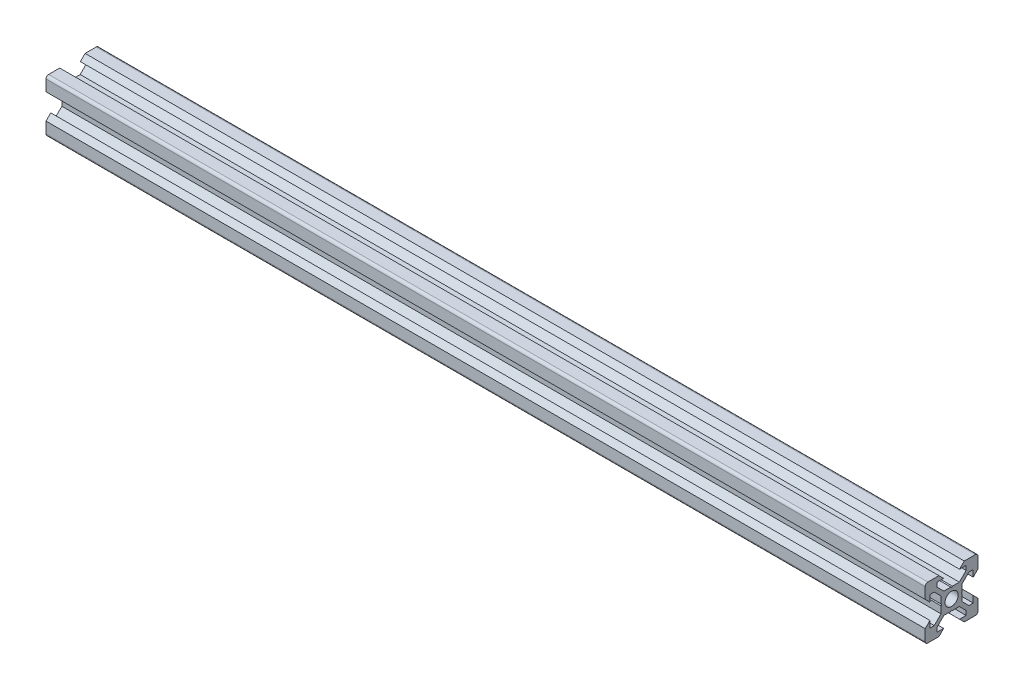
SolidWorks part; units mm, degrees
material "6063-T5"
material "6063-T5"
ref_plane "Plano frontal" through (0, 0, 0) normal (0, 0, 1) x (1, 0, 0)
ref_plane "Plano superior" through (0, 0, 0) normal (0, 1, 0) x (1, 0, 0)
ref_plane "Plano direito" through (0, 0, 0) normal (1, 0, 0) x (0, 0, -1)
sketch "Esboço1" plane through (0, 0, 0) normal (0, 0, 1) x (1, 0, 0)
  line L0 (0, 0) -> (333, 0)
  dimension "D1" = 333
other " C:\\USERS\\USER\\GOOGLE DRIVE\\13. INFORMAÇÕES TÉCNICAS\\BIBLIOTECA SERVIDOR\\PERFIS DE SOLDAGEM\\PERFIL ALUMÍNIO\\QUADRADO\\PF20-11 - PERFIL 2020 V-SLOT - IS MISSING(1)"
ref_plane "Plano1" through (0, 0, 0) normal (1, 0, 0) x (0, 1, 0)
sketch "Sketch11" plane through (0, 0, 0) normal (1, 0, 0) x (0, 1, 0)
  line L0 (-4.8, 10) -> (-3, 8.2)
  line L1 (-3, 8.2) -> (-5.5, 8.2)
  line L2 (-5.5, 8.2) -> (-5.5, 6.5607)
  line L3 (-5.5, 6.5607) -> (-2.9393, 4)
  line L4 (-2.9393, 4) -> (-0.3, 4)
  line L5 (5.5, 6.5607) -> (2.9393, 4)
  line L6 (5.5, 8.2) -> (5.5, 6.5607)
  line L7 (3, 8.2) -> (5.5, 8.2)
  line L8 (4.8, 10) -> (3, 8.2)
  line L9 (-0.3, 4) -> (0, 3.7)
  line L10 (0.3, 4) -> (0, 3.7)
  line L11 (0.3, 4) -> (2.9393, 4)
  line L12 (9, 10) -> (4.8, 10)
  line L13 (10, 4.8) -> (8.2, 3)
  line L14 (10, 4.8) -> (10, 9)
  line L15 (8.2, 3) -> (8.2, 5.5)
  line L16 (8.2, 5.5) -> (6.5607, 5.5)
  line L17 (6.5607, 5.5) -> (4, 2.9393)
  line L18 (4.8, -10) -> (3, -8.2)
  line L19 (3, -8.2) -> (5.5, -8.2)
  line L20 (5.5, -8.2) -> (5.5, -6.5607)
  line L21 (5.5, -6.5607) -> (2.9393, -4)
  line L22 (2.9393, -4) -> (0.3, -4)
  line L23 (0.3, -4) -> (0, -3.7)
  line L24 (-0.3, -4) -> (0, -3.7)
  line L25 (-0.3, -4) -> (-2.9393, -4)
  line L26 (-5.5, -6.5607) -> (-2.9393, -4)
  line L27 (-5.5, -8.2) -> (-5.5, -6.5607)
  line L28 (-3, -8.2) -> (-5.5, -8.2)
  line L29 (-4.8, -10) -> (-3, -8.2)
  line L30 (-10, -4.8) -> (-10, -9)
  line L31 (-10, -4.8) -> (-8.2, -3)
  line L32 (-8.2, -3) -> (-8.2, -5.5)
  line L33 (-8.2, -5.5) -> (-6.5607, -5.5)
  line L34 (-6.5607, -5.5) -> (-4, -2.9393)
  line L35 (-4, -2.9393) -> (-4, -0.3)
  line L36 (-4, -0.3) -> (-3.7, 0)
  line L37 (-4, 0.3) -> (-3.7, 0)
  line L38 (-4, 0.3) -> (-4, 2.9393)
  line L39 (-6.5607, 5.5) -> (-4, 2.9393)
  line L40 (-8.2, 5.5) -> (-6.5607, 5.5)
  line L41 (-8.2, 3) -> (-8.2, 5.5)
  line L42 (-10, 4.8) -> (-8.2, 3)
  line L43 (-4.8, 10) -> (-9, 10)
  line L44 (4, 2.9393) -> (4, 0.3)
  line L45 (4, 0.3) -> (3.7, 0)
  line L46 (4, -0.3) -> (3.7, 0)
  line L47 (4, -0.3) -> (4, -2.9393)
  line L48 (6.5607, -5.5) -> (4, -2.9393)
  line L49 (8.2, -5.5) -> (6.5607, -5.5)
  line L50 (8.2, -3) -> (8.2, -5.5)
  line L51 (10, -4.8) -> (8.2, -3)
  line L52 (10, -9) -> (10, -4.8)
  line L53 (4.8, -10) -> (9, -10)
  line L106 (-10, 9) -> (-10, 4.8)
  line L107 (-9, -10) -> (-4.8, -10)
  arc A0 (10, 9) -> (9, 10) centre (9, 9) ccw
  arc A1 (9, -10) -> (10, -9) centre (9, -9) ccw
  arc A3 (-10, -9) -> (-9, -10) centre (-9, -9) ccw
  arc A4 (-9, 10) -> (-10, 9) centre (-9, 9) ccw
  circle A7 centre (0, 0) radius 2.5
  point P1 (-10, 10)
  point P3 (10, 10)
  point P4 (10, -10)
  point P68 (0, 0)
  point P70 (10, 0)
  point P71 (0, 0)
  point P72 (0, 0)
  point P113 (0, -10)
  point P114 (-10, -10)
  point P115 (-10, 0)
  point P116 (0, 10)
  point P118 (0, 0)
sketch "Sketch12" plane through (0, 0, 0) normal (1, 0, 0) x (0, 0, -1)
  line B0 (10, -9) -> (10, -4.8)
  line B1 (10, -4.8) -> (8.2, -3)
  line B2 (8.2, -3) -> (8.2, -5.5)
  line B3 (8.2, -5.5) -> (6.5607, -5.5)
  line B4 (6.5607, -5.5) -> (4, -2.9393)
  line B5 (4, -2.9393) -> (4, -0.3)
  line B6 (4, -0.3) -> (3.7, 0)
  line B7 (3.7, 0) -> (4, 0.3)
  line B8 (4, 0.3) -> (4, 2.9393)
  line B9 (4, 2.9393) -> (6.5607, 5.5)
  line B10 (6.5607, 5.5) -> (8.2, 5.5)
  line B11 (8.2, 5.5) -> (8.2, 3)
  line B12 (8.2, 3) -> (10, 4.8)
  line B13 (10, 4.8) -> (10, 9)
  line B14 (9, 10) -> (4.8, 10)
  line B15 (4.8, 10) -> (3, 8.2)
  line B16 (3, 8.2) -> (5.5, 8.2)
  line B17 (5.5, 8.2) -> (5.5, 6.5607)
  line B18 (5.5, 6.5607) -> (2.9393, 4)
  line B19 (2.9393, 4) -> (0.3, 4)
  line B20 (0.3, 4) -> (0, 3.7)
  line B21 (0, 3.7) -> (-0.3, 4)
  line B22 (-0.3, 4) -> (-2.9393, 4)
  line B23 (-2.9393, 4) -> (-5.5, 6.5607)
  line B24 (-5.5, 6.5607) -> (-5.5, 8.2)
  line B25 (-5.5, 8.2) -> (-3, 8.2)
  line B26 (-3, 8.2) -> (-4.8, 10)
  line B27 (-4.8, 10) -> (-9, 10)
  line B28 (-10, 9) -> (-10, 4.8)
  line B29 (-10, 4.8) -> (-8.2, 3)
  line B30 (-8.2, 3) -> (-8.2, 5.5)
  line B31 (-8.2, 5.5) -> (-6.5607, 5.5)
  line B32 (-6.5607, 5.5) -> (-4, 2.9393)
  line B33 (-4, 2.9393) -> (-4, 0.3)
  line B34 (-4, 0.3) -> (-3.7, 0)
  line B35 (-3.7, 0) -> (-4, -0.3)
  line B36 (-4, -0.3) -> (-4, -2.9393)
  line B37 (-4, -2.9393) -> (-6.5607, -5.5)
  line B38 (-6.5607, -5.5) -> (-8.2, -5.5)
  line B39 (-8.2, -5.5) -> (-8.2, -3)
  line B40 (-8.2, -3) -> (-10, -4.8)
  line B41 (-10, -4.8) -> (-10, -9)
  line B42 (-9, -10) -> (-4.8, -10)
  line B43 (-4.8, -10) -> (-3, -8.2)
  line B44 (-3, -8.2) -> (-5.5, -8.2)
  line B45 (-5.5, -8.2) -> (-5.5, -6.5607)
  line B46 (-5.5, -6.5607) -> (-2.9393, -4)
  line B47 (-2.9393, -4) -> (-0.3, -4)
  line B48 (-0.3, -4) -> (0, -3.7)
  line B49 (0, -3.7) -> (0.3, -4)
  line B50 (0.3, -4) -> (2.9393, -4)
  line B51 (2.9393, -4) -> (5.5, -6.5607)
  line B52 (5.5, -6.5607) -> (5.5, -8.2)
  line B53 (5.5, -8.2) -> (3, -8.2)
  line B54 (3, -8.2) -> (4.8, -10)
  line B55 (4.8, -10) -> (9, -10)
  arc B56 (9, -10) -> (10, -9) centre (9, -9) ccw
  arc B57 (10, 9) -> (9, 10) centre (9, 9) ccw
  arc B58 (-9, 10) -> (-10, 9) centre (-9, 9) ccw
  arc B59 (-10, -9) -> (-9, -10) centre (-9, -9) ccw
sketch_block_instance "AL profile  block  -1"
sketch_block "AL profile  block  "
